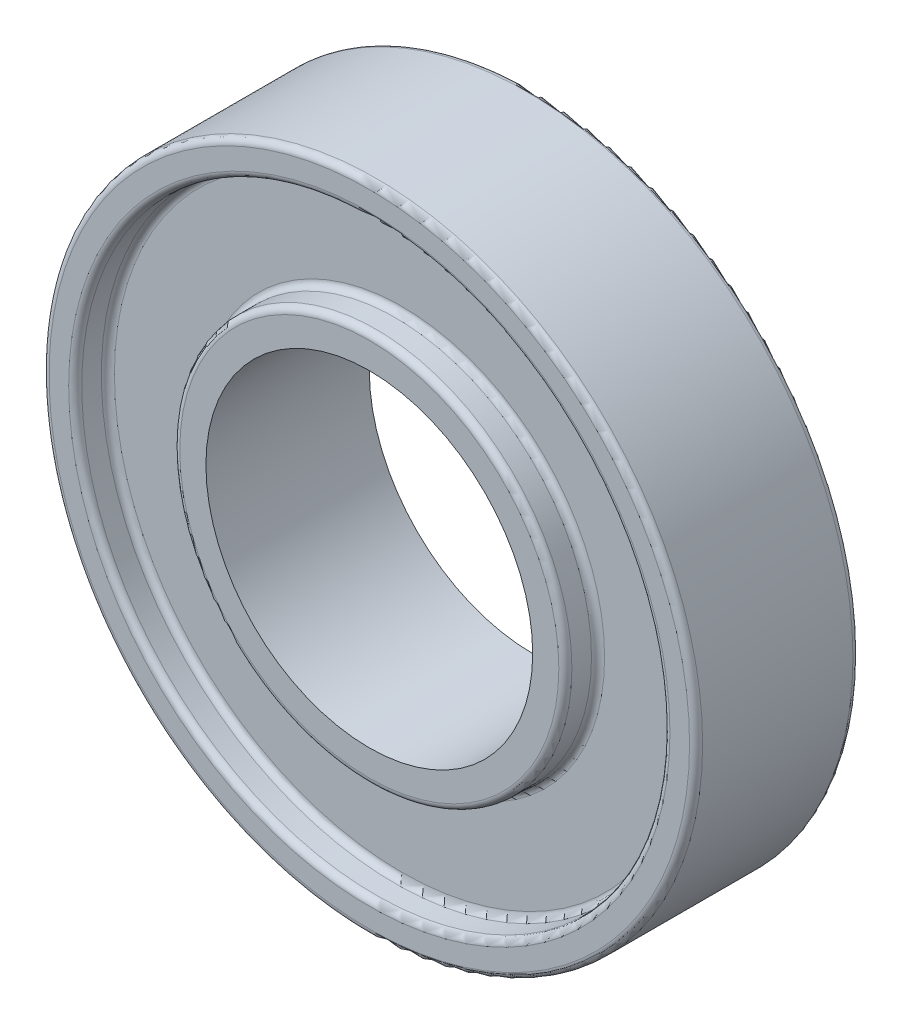
SolidWorks part; units mm, degrees
material "镀铬不锈钢"
ref_plane "前视基准面" through (0, 0, 0) normal (0, 0, 1) x (1, 0, 0)
ref_plane "上视基准面" through (0, 0, 0) normal (0, 1, 0) x (1, 0, 0)
ref_plane "右视基准面" through (0, 0, 0) normal (1, 0, 0) x (0, 0, -1)
other "Configuration Table"
sketch "草图1" plane through (0, 0, 0) normal (0, 0, 1) x (1, 0, 0)
  circle A0 centre (0, 0) radius 5
  circle A1 centre (0, 0) radius 10
  dimension "D1" = 10
  dimension "D2" = 20
extrude "凸台-拉伸1" add sketch "草图1" along normal blind 5
ref_plane "基准面1" through (0, 0, 2.5) normal (0, 0, 1) x (1, 0, 0)
sketch "草图3" plane through (0, 0, 5) normal (0, 0, 1) x (1, 0, 0)
  circle A0 centre (0, 0) radius 9
  circle A1 centre (0, 0) radius 6
  circle A2 centre (0, 0) radius 5 construction
  circle A3 centre (0, 0) radius 5 construction
  circle A4 centre (0, 0) radius 10 construction
  circle A5 centre (0, 0) radius 10 construction
  dimension "D1" = 1
  dimension "D2" = 1
extrude "切除-拉伸1" cut sketch "草图3" against normal blind 1
mirror "镜向1" about plane through (0, 0, 2.5) normal (0, 0, 1) of "切除-拉伸1"
fillet "圆角1" radius 0.2 10 edges at (9, 0, 4) (6, 0, 4) (10, 0, 0) (10, 0, 5) (9, 0, 5) (6, 0, 5) (9, 0, 0) (9, 0, 1) (6, 0, 0) (6, 0, 1)
